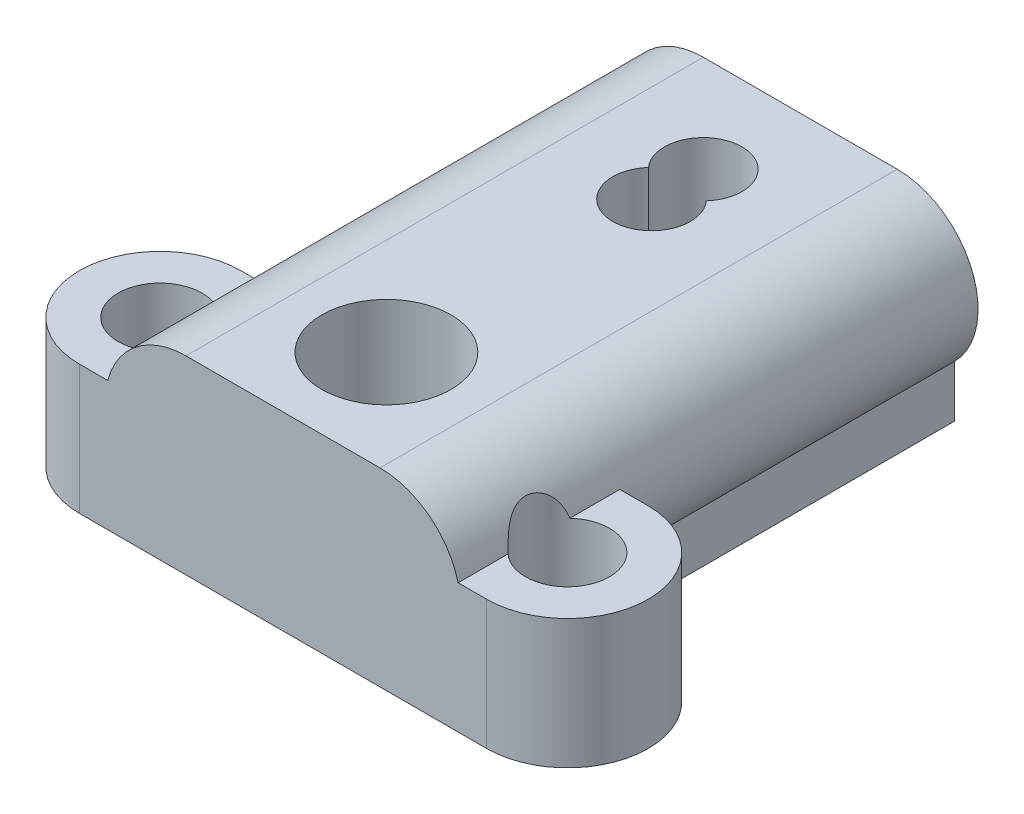
SolidWorks part; units mm, degrees
ref_plane "Front Plane" through (0, 0, 0) normal (0, 0, 1) x (1, 0, 0)
ref_plane "Top Plane" through (0, 0, 0) normal (0, 1, 0) x (1, 0, 0)
ref_plane "Right Plane" through (0, 0, 0) normal (1, 0, 0) x (0, 0, -1)
sketch "Sketch1" plane through (0, 0, 0) normal (0, 0, 1) x (1, 0, 0)
  line L0 (0, 0) -> (0, 16.1699) construction
  line L1 (-11.9194, 0) -> (11.9194, 0)
  line L2 (11.9194, 0) -> (11.9194, 4)
  line L6 (-11.9194, 0) -> (-11.9194, 4)
  line L7 (11.9194, 4) -> (10.151, 2.2316) construction
  line L8 (-7.5, 14.6694) -> (7.5, 14.6694)
  arc A0 (11.9194, 4) -> (7.5, 14.6694) centre (7.5, 8.4194) ccw
  circle A1 centre (7.5, 8.4194) radius 3.25
  arc A2 (-11.9194, 4) -> (-7.5, 14.6694) centre (-7.5, 8.4194) cw
  circle A3 centre (-7.5, 8.4194) radius 3.25
  point P7 (11.9194, 4.2515)
  point P24 (2.3156, 11.9101)
  dimension "D1" = 6.5
  dimension "D2" = 3
  dimension "D3" = 45
  dimension "D4" = 15
  dimension "D5" = 4
extrude "Boss-Extrude1" add sketch "Sketch1" along normal blind 40
sketch "Sketch10" plane through (0, 0, 40) normal (0, 0, 1) x (1, 0, 0)
  circle A0 centre (7.5, 8.4194) radius 3.25 construction
  circle A1 centre (-7.5, 8.4194) radius 3.25 construction
  circle A2 centre (7.5, 8.4194) radius 3.25
  circle A3 centre (-7.5, 8.4194) radius 3.25
extrude "Boss-Extrude2" add sketch "Sketch10" against normal offset from surface (30 mm away) 10 up to face at (10.75, 8.4194, 0)
sketch "Sketch2" plane through (0, 14.6694, 0) normal (0, 1, 0) x (1, 0, 0)
  line L0 (0, -7.5) -> (0, -11.5) construction
  line L1 (0, -11.5) -> (0, -32) construction
  line L2 (-7.5, -40) -> (7.5, -40) construction
  circle A0 centre (0, -7.5) radius 3
  circle A1 centre (0, -11.5) radius 3
  circle A2 centre (0, -32) radius 5
  line M5 (-7.5, -40) -> (7.5, -40)
  dimension "D4" = 6
  dimension "D5" = 10
  dimension "D1" = 20.5
  dimension "D2" = 4
  dimension "D3" = 8
extrude "Cut-Extrude1" cut sketch "Sketch2" against normal offset from surface (10.6694 mm away) 4 contours A0 A1 | A2 M5 up to face at (0, 0, 20)
sketch "Sketch8" plane through (0, 14.6694, 0) normal (0, 1, 0) x (1, 0, 0)
  circle A0 centre (0, -7.5) radius 1.6
  circle A1 centre (0, -11.5) radius 1.6
  circle A2 centre (0, -32) radius 2.6
  dimension "D1" = 5.2
  dimension "D2" = 3.2
extrude "Cut-Extrude2" cut sketch "Sketch8" against normal through all
sketch "Sketch11" plane through (0, 0, 0) normal (0, -1, 0) x (1, 0, 0)
  line L0 (11.9194, 40) -> (15.75, 40)
  line L1 (15.75, 27.5) -> (11.9194, 27.5)
  line L2 (11.9194, 40) -> (11.9194, 0) construction
  line L3 (11.9194, 27.5) -> (11.9194, 40)
  line L6 (0, 0) -> (0, 40) construction
  line L7 (-11.9194, 40) -> (11.9194, 40) construction
  line L8 (-11.9194, 27.5) -> (-11.9194, 40)
  line L9 (-15.75, 27.5) -> (-11.9194, 27.5)
  line L10 (-11.9194, 40) -> (-15.75, 40)
  arc A0 (15.75, 40) -> (15.75, 27.5) centre (15.75, 33.75) cw
  circle A1 centre (15.75, 33.75) radius 3.25
  circle A2 centre (-15.75, 33.75) radius 3.25
  arc A3 (-15.75, 40) -> (-15.75, 27.5) centre (-15.75, 33.75) ccw
  line M8 (11.9194, 0) -> (11.9194, 40)
  line M10 (-11.9194, 40) -> (-11.9194, 0)
  dimension "D1" = 6.5
  dimension "D2" = 3
  dimension "D3" = 31.5
extrude "Boss-Extrude3" add sketch "Sketch11" against normal blind 10 contours L10 A3 L9 A2 M10 | A0 L0 L1 A1 M8
sketch "Sketch12" plane through (0, 0, 0) normal (0, -1, 0) x (1, 0, 0)
  circle A0 centre (15.75, 33.75) radius 3.25 construction
  circle A1 centre (-15.75, 33.75) radius 3.25 construction
  circle A2 centre (15.75, 33.75) radius 3.25
  circle A3 centre (-15.75, 33.75) radius 3.25
extrude "Cut-Extrude3" cut sketch "Sketch12" against normal through all both and the other way through all
sketch "Sketch13" plane through (0, 0, 0) normal (0, -1, 0) x (1, 0, 0)
  circle A0 centre (15.75, 33.75) radius 3.25 construction
  circle A1 centre (-15.75, 33.75) radius 3.25 construction
  circle A2 centre (15.75, 33.75) radius 3.25
  circle A3 centre (-15.75, 33.75) radius 3.25
extrude "Boss-Extrude4" add sketch "Sketch13" against normal blind 2
